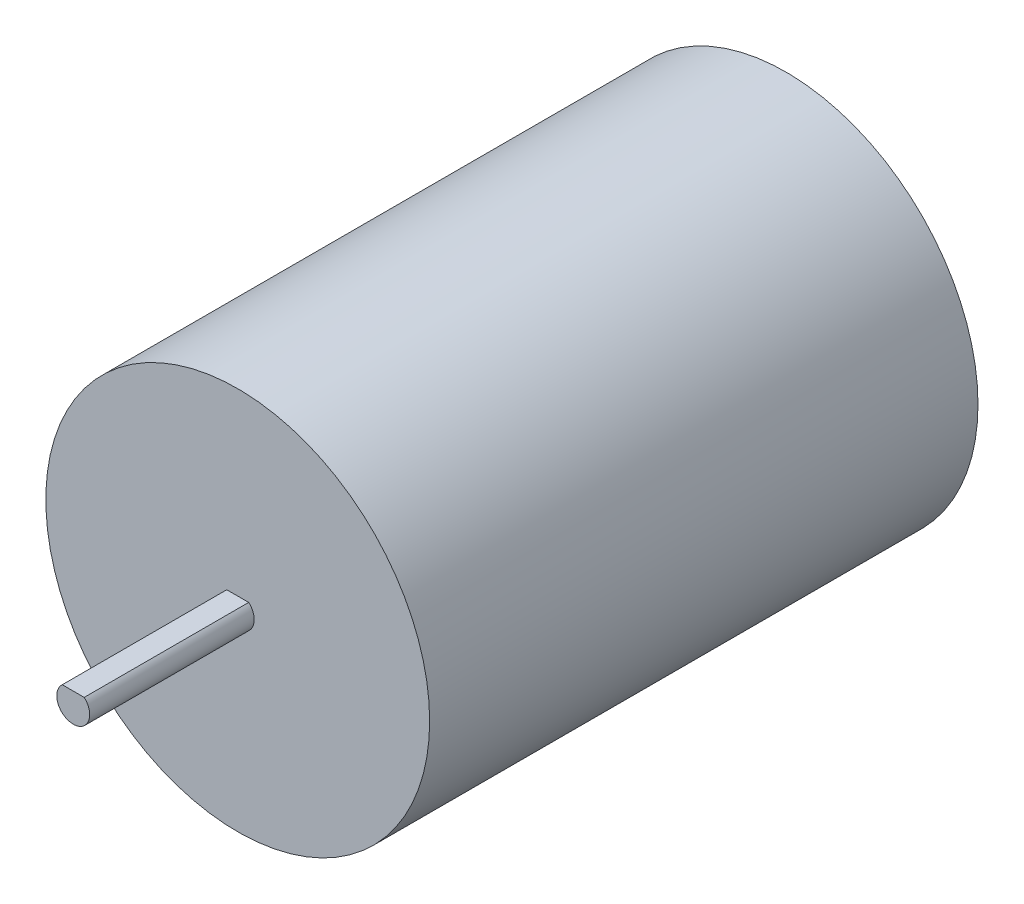
SolidWorks part; units mm, degrees
ref_plane "Front" through (0, 0, 0) normal (0, 0, 1) x (1, 0, 0)
ref_plane "Top" through (0, 0, 0) normal (0, 1, 0) x (1, 0, 0)
ref_plane "Right" through (0, 0, 0) normal (1, 0, 0) x (0, 0, -1)
sketch "Sketch1" plane through (0, 0, 0) normal (0, 0, 1) x (1, 0, 0)
  circle A0 centre (0, 0) radius 17.5
  dimension "D1" = 35
extrude "Boss-Extrude1" add sketch "Sketch1" along normal blind 50
sketch "Sketch7" plane through (0, 0, 50) normal (0, 0, 1) x (1, 0, 0)
  line L0 (-1, 1.118) -> (1, 1.118)
  arc A0 (-1, 1.118) -> (1, 1.118) centre (0, 0) ccw
  dimension "D1" = 3
  dimension "D2" = 2
extrude "Boss-Extrude5" add sketch "Sketch7" along normal blind 15
